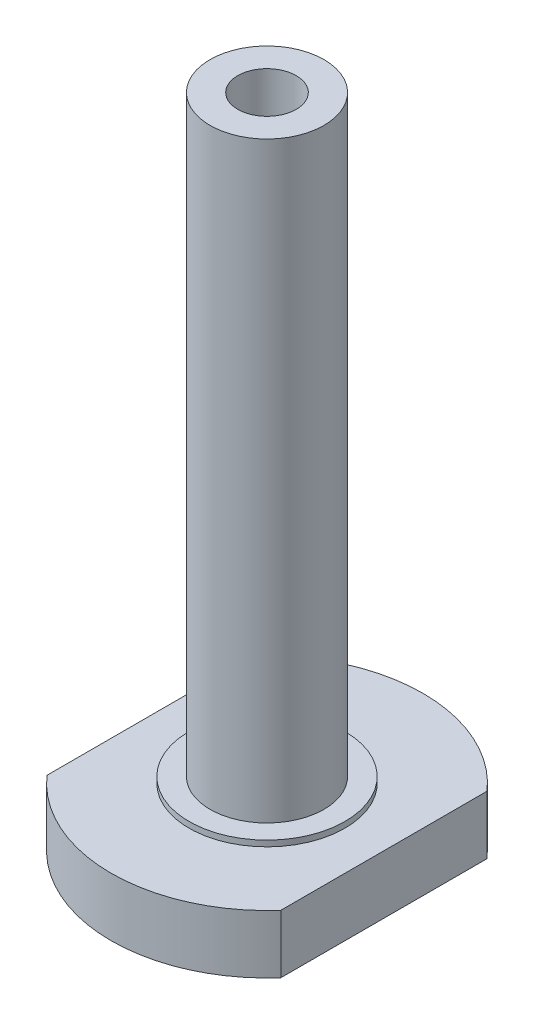
SolidWorks part; units mm, degrees
material "PET"
ref_plane "Plan de face" through (0, 0, 0) normal (0, 0, 1) x (1, 0, 0)
ref_plane "Plan de dessus" through (0, 0, 0) normal (0, 1, 0) x (1, 0, 0)
ref_plane "Plan de droite" through (0, 0, 0) normal (1, 0, 0) x (0, 0, -1)
sketch "Esquisse1" plane through (0, 0, 0) normal (0, 0, 1) x (1, 0, 0)
  line L0 (0, -3.6646) -> (0, 30.4689) construction
  line L1 (-1.5, 0) -> (-1.5, 33.7)
  line L2 (-1.5, 33.7) -> (-2.925, 33.7)
  line L3 (-2.925, 33.7) -> (-2.925, 3.3)
  line L4 (-2.925, 3.3) -> (-4, 3.3)
  line L5 (-4, 3.3) -> (-4, 3)
  line L6 (-4, 3) -> (-8, 3)
  line L7 (-8, 3) -> (-8, 0)
  line L8 (-8, 0) -> (-1.5, 0)
  dimension "D1" = 3
  dimension "D2" = 16
  dimension "D3" = 0.3
  dimension "D4" = 8
  dimension "D5" = 33.7
  dimension "D6" = 3
  dimension "D7" = 5.85
revolve "Révolution1" add sketch "Esquisse1" angle 360 about L0
sketch "Esquisse2" plane through (0, 0, 0) normal (0, -1, 0) x (1, 0, 0)
  line L0 (0, 8.5631) -> (0, -8.4906) construction
  line L1 (-6, 5.2915) -> (-6, -5.2915)
  line L2 (6, 5.2915) -> (6, -5.2915)
  circle A2 centre (0, 0) radius 8 construction
  arc A3 (-6, 5.2915) -> (-6, -5.2915) centre (0, 0) ccw
  arc A4 (6, 5.2915) -> (6, -5.2915) centre (0, 0) cw
  circle M4 centre (0, 0) radius 8
  dimension "D1" = 12
extrude "Enlèv. mat.-Extru.1" cut sketch "Esquisse2" against normal up to next contours L2 M4 | L1 M4
